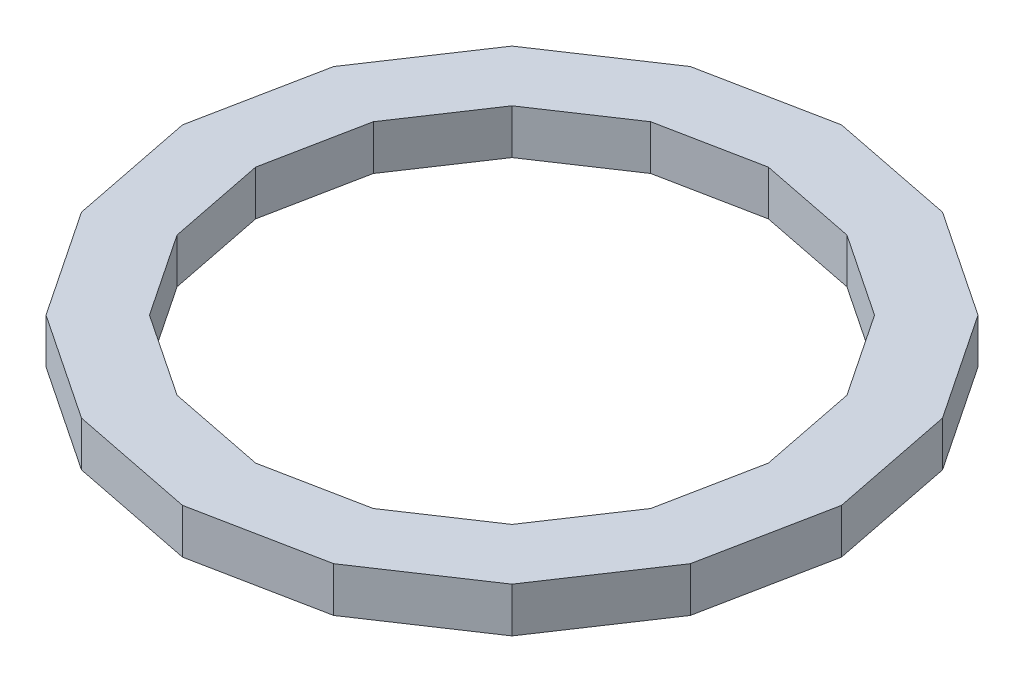
SolidWorks part; units mm, degrees
ref_plane "Front Plane" through (0, 0, 0) normal (0, 0, 1) x (1, 0, 0)
ref_plane "Top Plane" through (0, 0, 0) normal (0, 1, 0) x (1, 0, 0)
ref_plane "Right Plane" through (0, 0, 0) normal (1, 0, 0) x (0, 0, -1)
sketch "Sketch1" plane through (0, 0, 0) normal (0, 1, 0) x (1, 0, 0)
  line L1 (108.8837, 0) -> (100.5954, 41.668)
  line L2 (100.5954, 41.668) -> (76.9924, 76.9924)
  line L3 (76.9924, 76.9924) -> (41.668, 100.5954)
  line L4 (41.668, 100.5954) -> (0, 108.8837)
  line L5 (0, 108.8837) -> (-41.668, 100.5954)
  line L6 (-41.668, 100.5954) -> (-76.9924, 76.9924)
  line L7 (-76.9924, 76.9924) -> (-100.5954, 41.668)
  line L8 (-100.5954, 41.668) -> (-108.8837, 0)
  line L9 (-108.8837, 0) -> (-100.5954, -41.668)
  line L10 (-100.5954, -41.668) -> (-76.9924, -76.9924)
  line L11 (-76.9924, -76.9924) -> (-41.668, -100.5954)
  line L12 (-41.668, -100.5954) -> (0, -108.8837)
  line L13 (0, -108.8837) -> (41.668, -100.5954)
  line L14 (41.668, -100.5954) -> (76.9924, -76.9924)
  line L15 (76.9924, -76.9924) -> (100.5954, -41.668)
  line L16 (100.5954, -41.668) -> (108.8837, 0)
  line L17 (139.9608, 0) -> (129.3069, 53.5607)
  line L18 (129.3069, 53.5607) -> (98.9672, 98.9672)
  line L19 (98.9672, 98.9672) -> (53.5607, 129.3069)
  line L20 (53.5607, 129.3069) -> (0, 139.9608)
  line L21 (0, 139.9608) -> (-53.5607, 129.3069)
  line L22 (-53.5607, 129.3069) -> (-98.9672, 98.9672)
  line L23 (-98.9672, 98.9672) -> (-129.3069, 53.5607)
  line L24 (-129.3069, 53.5607) -> (-139.9608, 0)
  line L25 (-139.9608, 0) -> (-129.3069, -53.5607)
  line L26 (-129.3069, -53.5607) -> (-98.9672, -98.9672)
  line L27 (-98.9672, -98.9672) -> (-53.5607, -129.3069)
  line L28 (-53.5607, -129.3069) -> (0, -139.9608)
  line L29 (0, -139.9608) -> (53.5607, -129.3069)
  line L30 (53.5607, -129.3069) -> (98.9672, -98.9672)
  line L31 (98.9672, -98.9672) -> (129.3069, -53.5607)
  line L32 (129.3069, -53.5607) -> (139.9608, 0)
  circle A0 centre (0, 0) radius 106.7915 construction
  circle A1 centre (0, 0) radius 137.2715 construction
  dimension "D1" = 30.48
  dimension "D2" = 54.61
extrude "Boss-Extrude1" add sketch "Sketch1" along normal blind 19.05
